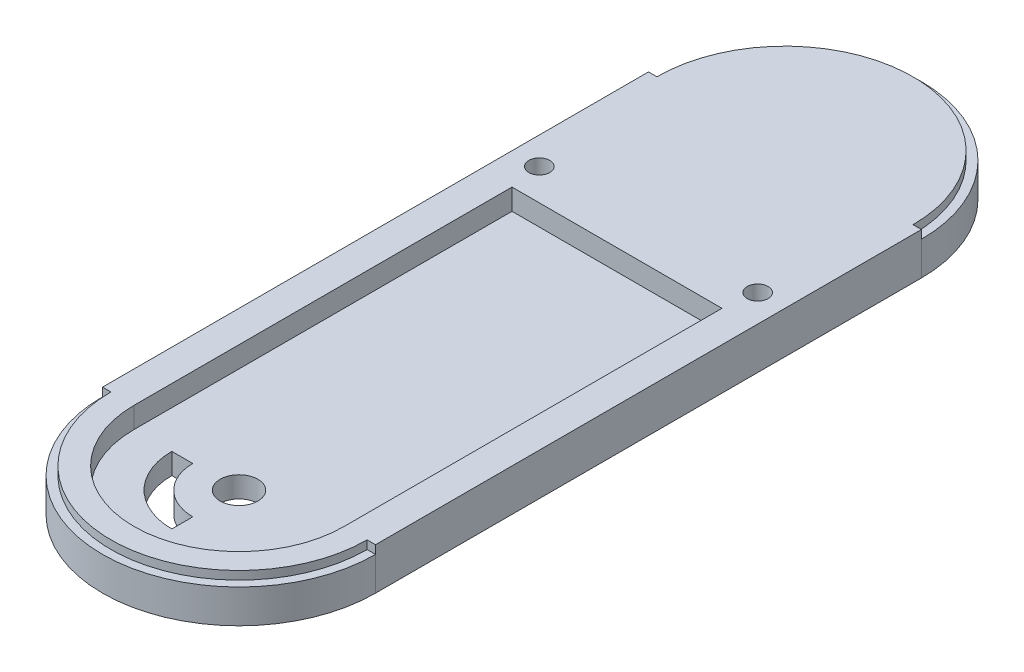
SolidWorks part; units mm, degrees
ref_plane "Front Plane" through (0, 0, 0) normal (0, 0, 1) x (1, 0, 0)
ref_plane "Top Plane" through (0, 0, 0) normal (0, 1, 0) x (1, 0, 0)
ref_plane "Right Plane" through (0, 0, 0) normal (1, 0, 0) x (0, 0, -1)
sketch "Sketch1" plane through (0, 0, 0) normal (0, 1, 0) x (1, 0, 0)
  line L0 (0, 97.5) -> (0, 65) construction
  line L2 (-32.5, 65) -> (-32.5, -65)
  line L4 (32.5, 65) -> (32.5, -65)
  line L5 (-27.4608, 82.3825) -> (27.4608, -82.3825) construction
  line L6 (-27.4608, -82.3825) -> (27.4608, 82.3825) construction
  line L7 (0, -97.5) -> (0, -65) construction
  arc A0 (-32.5, 65) -> (32.5, 65) centre (0, 65) cw
  arc A1 (32.5, -65) -> (-32.5, -65) centre (0, -65) cw
  point P0 (0, 0)
extrude "Boss-Extrude1" add sketch "Sketch1" along normal blind 10
sketch "Sketch6" plane through (0, 10, 0) normal (0, 1, 0) x (1, 0, 0)
  line L0 (-25, -65) -> (-25, 25)
  line L1 (-25, 25) -> (25, 25)
  line L2 (25, 25) -> (25, -65)
  arc A0 (25, -65) -> (-25, -65) centre (0, -65) cw
extrude "Cut-Extrude4" cut sketch "Sketch6" against normal blind 5
sketch "Sketch7" plane through (0, 5, 0) normal (0, 1, 0) x (1, 0, 0)
  circle A0 centre (0, -65) radius 4.5
extrude "Cut-Extrude5" cut sketch "Sketch7" against normal blind 5
sketch "Sketch8" plane through (0, 5, 0) normal (0, 1, 0) x (1, 0, 0)
  line L0 (-16, -65) -> (-11, -65)
  line L1 (0, -76) -> (0, -81)
  arc A0 (-11, -65) -> (0, -76) centre (0, -65) ccw
  arc A1 (-16, -65) -> (0, -81) centre (0, -65) ccw
extrude "Cut-Extrude6" cut sketch "Sketch8" against normal blind 10
sketch "Sketch9" plane through (0, 10, 0) normal (0, 1, 0) x (1, 0, 0)
  line L0 (-32.5, -65) -> (-30.5, -65)
  line L1 (30.5, -65) -> (32.5, -65)
  line L2 (-32.5, 65) -> (-32.5, -65)
  line L3 (32.5, -65) -> (32.5, 65)
  line L6 (-30.5, 65) -> (-32.5, 65)
  line L7 (30.5, 65) -> (32.5, 65)
  arc A0 (-30.5, 65) -> (30.5, 65) centre (0, 65) cw
  arc A1 (-30.5, -65) -> (30.5, -65) centre (0, -65) ccw
  arc A2 (32.5, 65) -> (-32.5, 65) centre (0, 65) ccw
  arc A3 (-32.5, -65) -> (32.5, -65) centre (0, -65) ccw
  arc A4 (32.5, 65) -> (-32.5, 65) centre (0, 65) ccw
  arc A5 (-32.5, -65) -> (32.5, -65) centre (0, -65) ccw
  dimension "D1" = 0
extrude "Cut-Extrude7" cut sketch "Sketch9" against normal blind 2
sketch "Sketch11" plane through (0, 10, 0) normal (0, 1, 0) x (1, 0, 0)
  line L0 (-26, 32.5) -> (26, 32.5) construction
  circle A0 centre (0, 65) radius 32.5 construction
  circle A1 centre (26, 32.5) radius 2.5
  circle A2 centre (-26, 32.5) radius 2.5
  point P7 (0, 32.5)
extrude "Cut-Extrude8" cut sketch "Sketch11" against normal through all
